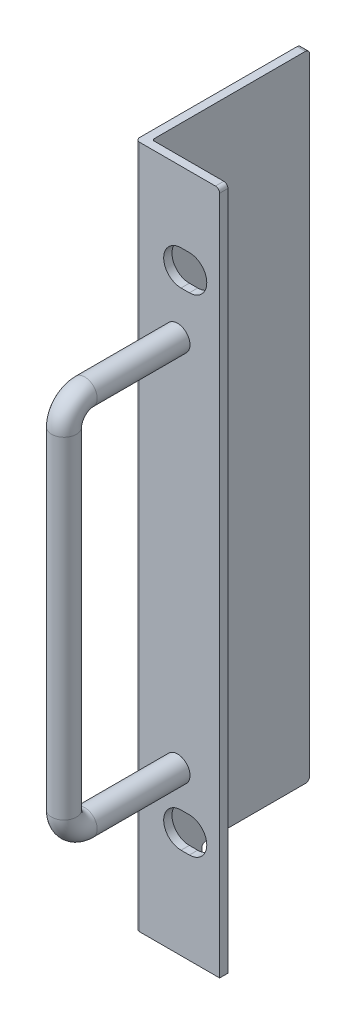
SolidWorks part; units mm, degrees
ref_plane "Front Plane" through (0, 0, 0) normal (0, 0, 1) x (1, 0, 0)
ref_plane "Top Plane" through (0, 0, 0) normal (0, 1, 0) x (1, 0, 0)
ref_plane "Right Plane" through (0, 0, 0) normal (1, 0, 0) x (0, 0, -1)
sketch "Sketch1" plane through (0, 0, 0) normal (0, 1, 0) x (1, 0, 0)
  line L2 (0, 0) -> (0, 40)
  line L3 (0, 40) -> (2, 40)
  line L4 (2, 2) -> (2, 40)
  line L5 (0, 0) -> (20.3, 0)
  line L7 (2, 2) -> (20.3, 2)
  line L8 (20.3, 0) -> (20.3, 2)
  dimension "D1" = 20.3
  dimension "D2" = 2
  dimension "D3" = 2
  dimension "D4" = 40
extrude "Boss-Extrude1" add sketch "Sketch1" along normal blind 165
sketch "Sketch2" plane through (0, 0, 0) normal (0, 0, 1) x (1, 0, 0)
  line L0 (12, 165) -> (12, 0) construction
  line L1 (0, 165) -> (20.3, 165) construction
  line L2 (0, 0) -> (20.3, 0) construction
  line L5 (20.3, 165) -> (20.3, 0) construction
  line L6 (13, 143.745) -> (11, 143.745) construction
  line L7 (13, 139.545) -> (11, 139.545)
  line L8 (13, 147.945) -> (11, 147.945)
  line L9 (13, 26.255) -> (11, 26.255) construction
  line L10 (13, 30.455) -> (11, 30.455)
  line L11 (13, 22.055) -> (11, 22.055)
  arc A0 (13, 139.545) -> (13, 147.945) centre (13, 143.745) ccw
  arc A1 (11, 147.945) -> (11, 139.545) centre (11, 143.745) ccw
  arc A2 (13, 30.455) -> (13, 22.055) centre (13, 26.255) cw
  arc A3 (11, 22.055) -> (11, 30.455) centre (11, 26.255) cw
  point P14 (12, 143.745)
  point P19 (6.8, 143.745)
  point P20 (17.2, 143.745)
  point P23 (12, 26.255)
  dimension "D4" = 117.49
  dimension "D1" = 8.4
  dimension "D2" = 10.4
  dimension "D3" = 8.3
  dimension "D5" = 21.255
extrude "Cut-Extrude1" cut sketch "Sketch2" against normal blind 132
sketch "Sketch3" plane through (0, 0, 0) normal (0, 0, 1) x (1, 0, 0)
  line L0 (10.15, 165) -> (10.15, 0) construction
  line L1 (0, 165) -> (20.3, 165) construction
  line L2 (0, 0) -> (20.3, 0) construction
ref_plane "Plane1" through (10.15, 0, 0) normal (1, 0, 0) x (0, 0, -1)
sketch "Sketch4" plane through (10.15, 0, 0) normal (1, 0, 0) x (0, 0, -1)
  line L0 (0, 128.745) -> (-27.4, 128.745) construction
  line L1 (0, 165) -> (0, 0) construction
  line L2 (-27.4, 128.745) -> (-27.4, 38.745) construction
  line L3 (-27.4, 83.745) -> (0, 83.745) construction
  line L4 (0, 38.745) -> (-27.4, 38.745) construction
  line L5 (0, 147.945) -> (0, 139.545) construction
  line L6 (0, 128.745) -> (-22.4, 128.745)
  line L7 (-27.4, 123.745) -> (-27.4, 43.745)
  line L8 (0, 38.745) -> (-22.4, 38.745)
  arc A0 (-22.4, 128.745) -> (-27.4, 123.745) centre (-22.4, 123.745) ccw
  arc A1 (-22.4, 38.745) -> (-27.4, 43.745) centre (-22.4, 43.745) cw
  point P10 (0, 143.745)
  dimension "D3" = 5
  dimension "D1" = 15
  dimension "D2" = 27.4
  dimension "D4" = 90
sketch "Sketch5" plane through (0, 0, 0) normal (0, 0, 1) x (1, 0, 0)
  circle A0 centre (10.15, 128.745) radius 3
  dimension "D1" = 6
sweep "Sweep1" add profiles "Sketch5" path "Sketch4"
sketch "Sketch6" plane through (2, 0, 0) normal (1, 0, 0) x (0, 0, -1)
  line L0 (2, 82.5) -> (40, 82.5) construction
  line L1 (40, 0) -> (14, 0)
  line L2 (40, 0) -> (40, 12)
  line L3 (40, 12) -> (14, 12)
  line L4 (14, 0) -> (14, 12)
  line L5 (2, 165) -> (2, 0) construction
  line L6 (40, 165) -> (40, 0) construction
  line L7 (14, 165) -> (14, 153) construction
  line L8 (40, 153) -> (14, 153) construction
  line L9 (40, 165) -> (40, 153) construction
  line L10 (40, 165) -> (14, 165) construction
  dimension "D1" = 12
  dimension "D2" = 12
extrude "Cut-Extrude2" cut sketch "Sketch6" against normal blind 132
fillet "Fillet1" radius 1 6 edges at (0, 82.5, 0) (20.3, 165, -1) (1, 165, -40) (1, 12, -40) (1, 12, -14) (1, 0, -14)
fillet "Fillet2" radius 0.5 1 edges at (2, 82.5, -2)
